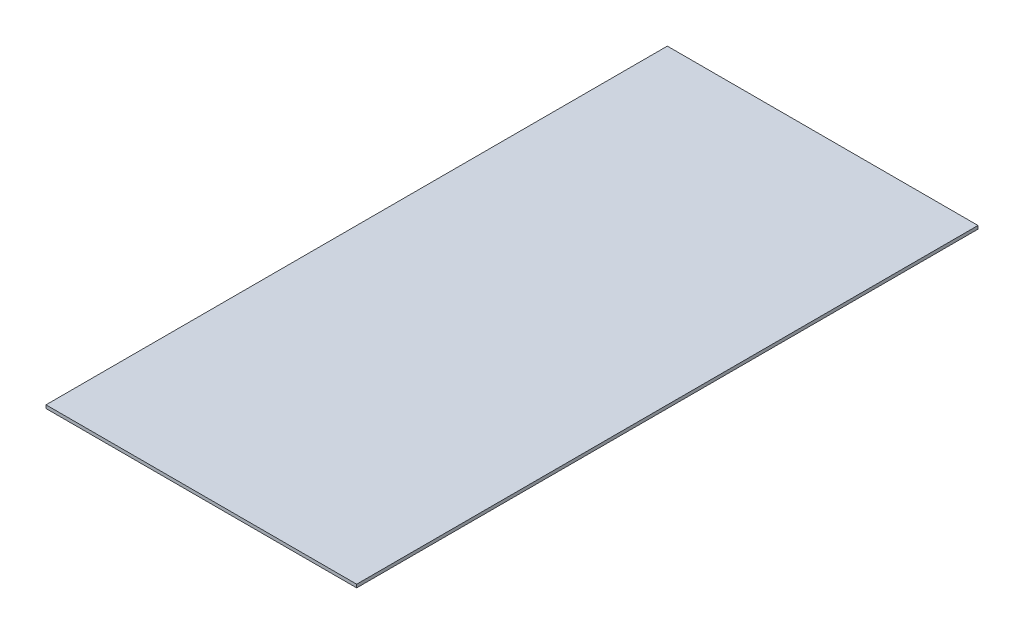
SolidWorks part; units mm, degrees
ref_plane "Front Plane" through (0, 0, 0) normal (0, 0, 1) x (1, 0, 0)
ref_plane "Top Plane" through (0, 0, 0) normal (0, 1, 0) x (1, 0, 0)
ref_plane "Right Plane" through (0, 0, 0) normal (1, 0, 0) x (0, 0, -1)
sketch "Sketch1" plane through (0, 0, 0) normal (0, 1, 0) x (1, 0, 0)
  line L1 (0, 0) -> (1219.2, 0)
  line L2 (0, 0) -> (0, 2438.4)
  line L3 (0, 2438.4) -> (1219.2, 2438.4)
  line L4 (1219.2, 0) -> (1219.2, 2438.4)
  dimension "D1" = 1219.2
  dimension "D2" = 2438.4
extrude "Boss-Extrude1" add sketch "Sketch1" along normal blind 12.7
sketch "Sketch2" plane through (0, 12.7, 0) normal (0, 1, 0) x (1, 0, 0)
  line L0 (0, 2438.4) -> (1219.2, 0) construction
  line L1 (279.4, 2099.31) -> (939.8, 2099.31)
  line L2 (279.4, 2099.31) -> (279.4, 339.09)
  line L3 (279.4, 339.09) -> (939.8, 339.09)
  line L4 (939.8, 2099.31) -> (939.8, 339.09)
  line L5 (1219.2, 2438.4) -> (0, 0) construction
  line L6 (279.4, 1219.2) -> (939.8, 1219.2) construction
  point P14 (609.6, 1219.2)
  point P15 (609.6, 1219.2)
  dimension "D1" = 660.4
  dimension "D2" = 1760.22
